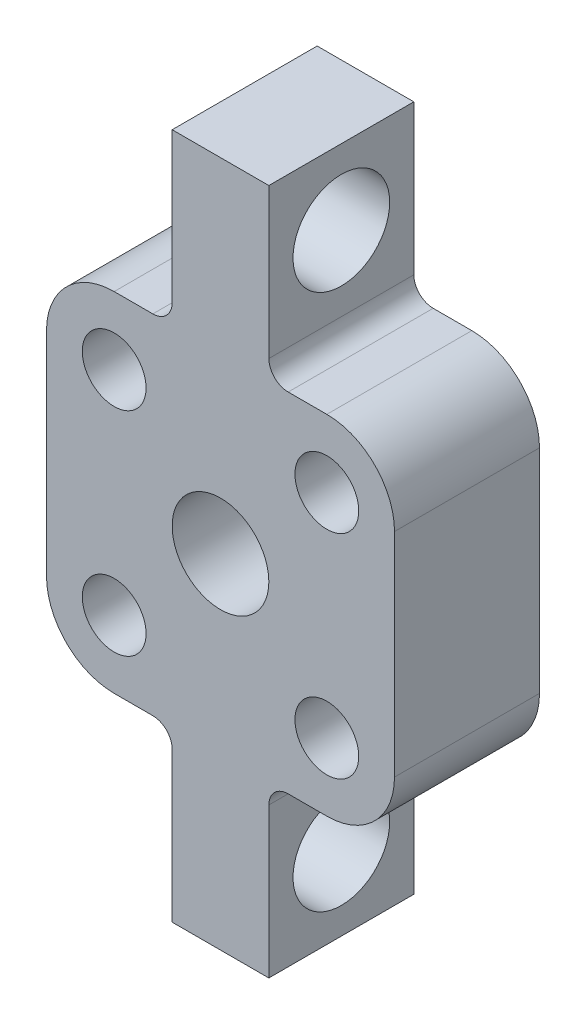
SolidWorks part; units mm, degrees
material "ASTM A36 Aço"
ref_plane "Plano frontal" through (0, 0, 0) normal (0, 0, 1) x (1, 0, 0)
ref_plane "Plano superior" through (0, 0, 0) normal (0, 1, 0) x (1, 0, 0)
ref_plane "Plano direito" through (0, 0, 0) normal (1, 0, 0) x (0, 0, -1)
sketch "Esboço1" plane through (0, 0, 0) normal (0, 0, 1) x (1, 0, 0)
  line L0 (-5, -20) -> (-5, -35.5)
  line L1 (-11, 18) -> (-7, 18)
  line L2 (-18, 11) -> (-18, -11)
  line L3 (-11, -18) -> (-7, -18)
  line L4 (18, 11) -> (18, -11)
  line L5 (-5, -35.5) -> (5, -35.5)
  line L6 (5, -35.5) -> (5, -20)
  line L7 (7, -18) -> (11, -18)
  line L8 (-18, 0) -> (18, 0) construction
  line L9 (5, 35.5) -> (5, 20)
  line L10 (-5, 20) -> (-5, 35.5)
  line L11 (-5, 35.5) -> (5, 35.5)
  line L12 (7, 18) -> (11, 18)
  line L13 (0, 35.5) -> (0, -35.5) construction
  circle A0 centre (0, 0) radius 5
  arc A1 (-11, 18) -> (-18, 11) centre (-11, 11) ccw
  arc A2 (11, 18) -> (18, 11) centre (11, 11) cw
  arc A3 (11, -18) -> (18, -11) centre (11, -11) ccw
  arc A4 (-11, -18) -> (-18, -11) centre (-11, -11) cw
  arc A5 (7, -18) -> (5, -20) centre (7, -20) ccw
  arc A6 (-7, -18) -> (-5, -20) centre (-7, -20) cw
  arc A7 (-7, 18) -> (-5, 20) centre (-7, 20) ccw
  arc A8 (7, 18) -> (5, 20) centre (7, 20) cw
  point P6 (-18, 0)
  point P22 (0, -35.5)
  point P25 (5, -18)
  point P28 (-5, -18)
  point P38 (0, 35.5)
  point P52 (0, 0)
  dimension "D1" = 10
  dimension "D3" = 7
  dimension "D6" = 2
  dimension "D7" = 22
  dimension "D2" = 36
  dimension "D4" = 10
  dimension "D5" = 17.5
extrude "Ressalto-extrusão1" add sketch "Esboço1" along normal blind 15
hole_wizard "Furo com folga de M61" positions "Esboço2" profile "Esboço3" hole size "M6" standard "ISO" end condition through all
sketch "Esboço2" plane through (0, 0, 15) normal (0, 0, 1) x (1, 0, 0)
  line L0 (18, -11) -> (18, 11) construction
  line L1 (11, 18) -> (7, 18) construction
  line L2 (7, -18) -> (11, -18) construction
  line L3 (-18, 11) -> (-18, -11) construction
  point P0 (11, 11)
  point P2 (-11, 11)
  point P4 (-11, -11)
  point P6 (11, -11)
  dimension "D1" = 7
  dimension "D2" = 7
  dimension "D3" = 7
  dimension "D4" = 7
sketch "Esboço3" plane through (11, 11, 15) normal (1, 0, 0) x (0, -1, 0)
  line L0 (0, 0) -> (0, 15)
  line L1 (0, 15) -> (3.3, 15)
  line L2 (3.3, 15) -> (3.3, 0)
  line L5 (3.3, 0) -> (0, 0)
  line L11 (0, -6.35) -> (0, 107.95) construction
  dimension "Thru Hole Dia." = 6.6
  dimension "Thru Hole Depth" = 15
sketch "Esboço4" plane through (0, 0, 0) normal (1, 0, 0) x (0, 0, -1)
  line L0 (0, 20) -> (0, 35.5) construction
  line L2 (-15, 20) -> (0, 20) construction
  line L3 (0, 0) -> (-15, 0) construction
  line L4 (-15, -11) -> (-15, 11) construction
  circle A0 centre (-7.5, 27.75) radius 5
  circle A1 centre (-7.5, -27.75) radius 5
  dimension "D1" = 7.5
  dimension "D3" = 10
  dimension "D2" = 7.75
extrude "Corte-extrusão1" cut sketch "Esboço4" along normal through all both and the other way through all
